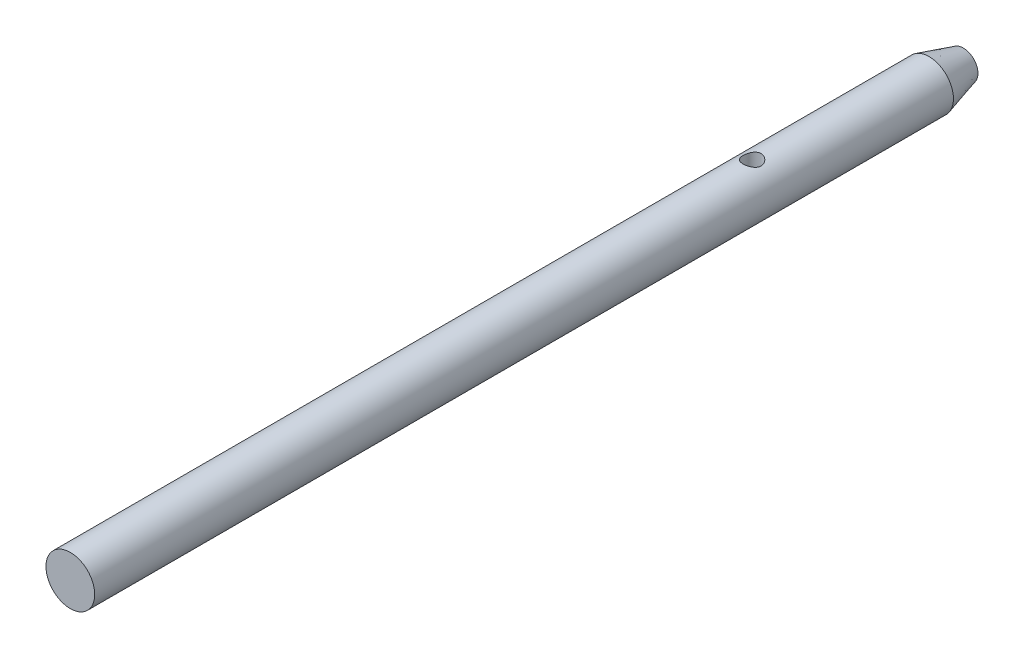
SolidWorks part; units mm, degrees
ref_plane "Plane1" through (0, 0, 0) normal (0, 0, 1) x (1, 0, 0)
ref_plane "Plane2" through (0, 0, 0) normal (0, 1, 0) x (1, 0, 0)
ref_plane "Plane3" through (0, 0, 0) normal (1, 0, 0) x (0, 0, -1)
other "Configuration Table"
sketch "Sketch1" plane through (0, 0, 0) normal (0, 0, 1) x (1, 0, 0)
  circle A0 centre (0, 0) radius 2.135
  dimension "D1" = 4.27
extrude "drive shaft shape" add sketch "Sketch1" along normal blind 78.2
cosmetic thread "Cosmetic Thread1"
chamfer "drive shaft chamfer" distance 0.85 distance2 3 1 edges at (2.135, 0, 0)
sketch "Sketch2" plane through (0, 0, 0) normal (0, 1, 0) x (1, 0, 0)
  line L0 (0, 0) -> (0, -88.6602) construction
  line L1 (0, -78.2) -> (0, -3) construction
  circle A0 centre (0, -18.5) radius 0.79
  dimension "D2" = 1.58
  dimension "D1" = 18.5
extrude "drive shaft pin hole" cut sketch "Sketch2" against normal up to next and the other way up to next
